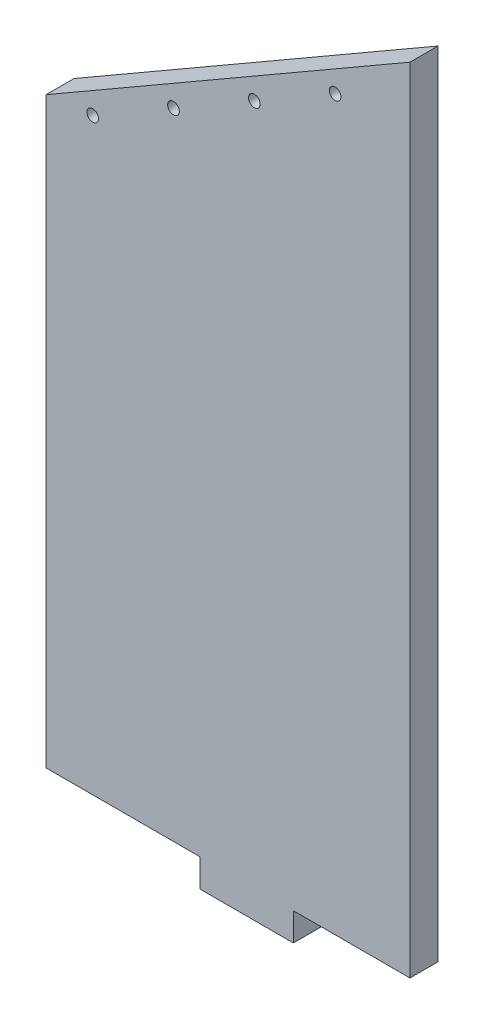
SolidWorks part; units mm, degrees
ref_plane "Plan de face" through (0, 0, 0) normal (0, 0, 1) x (1, 0, 0)
ref_plane "Plan de dessus" through (0, 0, 0) normal (0, 1, 0) x (1, 0, 0)
ref_plane "Plan de droite" through (0, 0, 0) normal (1, 0, 0) x (0, 0, -1)
sketch "Esquisse1" plane through (0, 0, 0) normal (0, 0, 1) x (1, 0, 0)
  line L0 (-78, 0) -> (-78, 124.9667)
  line L1 (0, 0) -> (-78, 0)
  line L2 (0, 0) -> (0, 170)
  line L3 (-78, 124.9667) -> (0, 170)
  dimension "D1" = 120
  dimension "D2" = 78
  dimension "D3" = 170
extrude "Boss.-Extru.1" add sketch "Esquisse1" along normal blind 6
sketch "Esquisse2" plane through (0, 0, 6) normal (0, 0, 1) x (1, 0, 0)
  line L0 (0, 170) -> (-78, 124.9667) construction
  line L1 (-78, 124.9667) -> (-78, 0) construction
  circle A0 centre (-68, 126.1214) radius 1.25
  circle A1 centre (-50.6795, 136.1214) radius 1.25
  circle A2 centre (-16.0385, 156.1214) radius 1.25
  circle A3 centre (-33.359, 146.1214) radius 1.25
  dimension "D1" = 2.5
  dimension "D2" = 2.5
  dimension "D3" = 2.5
  dimension "D5" = 4
  dimension "D10" = 2.5
  dimension "D4" = 4
  dimension "D6" = 4
  dimension "D7" = 10
  dimension "D8" = 20
  dimension "D9" = 20
  dimension "D11" = 4
  dimension "D12" = 20
extrude "Enlèv. mat.-Extru.1" cut sketch "Esquisse2" against normal blind 10
sketch "Esquisse4" plane through (0, 0, 0) normal (0, -1, 0) x (1, 0, 0)
  line L0 (-78, 0) -> (0, 0) construction
  line L1 (-25, 0) -> (-45, 0)
  line L2 (-25, 0) -> (-25, 6)
  line L3 (-25, 6) -> (-45, 6)
  line L4 (-45, 0) -> (-45, 6)
  line L5 (-78, 6) -> (0, 6) construction
  line L6 (0, 6) -> (0, 0) construction
  dimension "D1" = 20
  dimension "D2" = 25
extrude "Boss.-Extru.2" add sketch "Esquisse4" along normal blind 6
